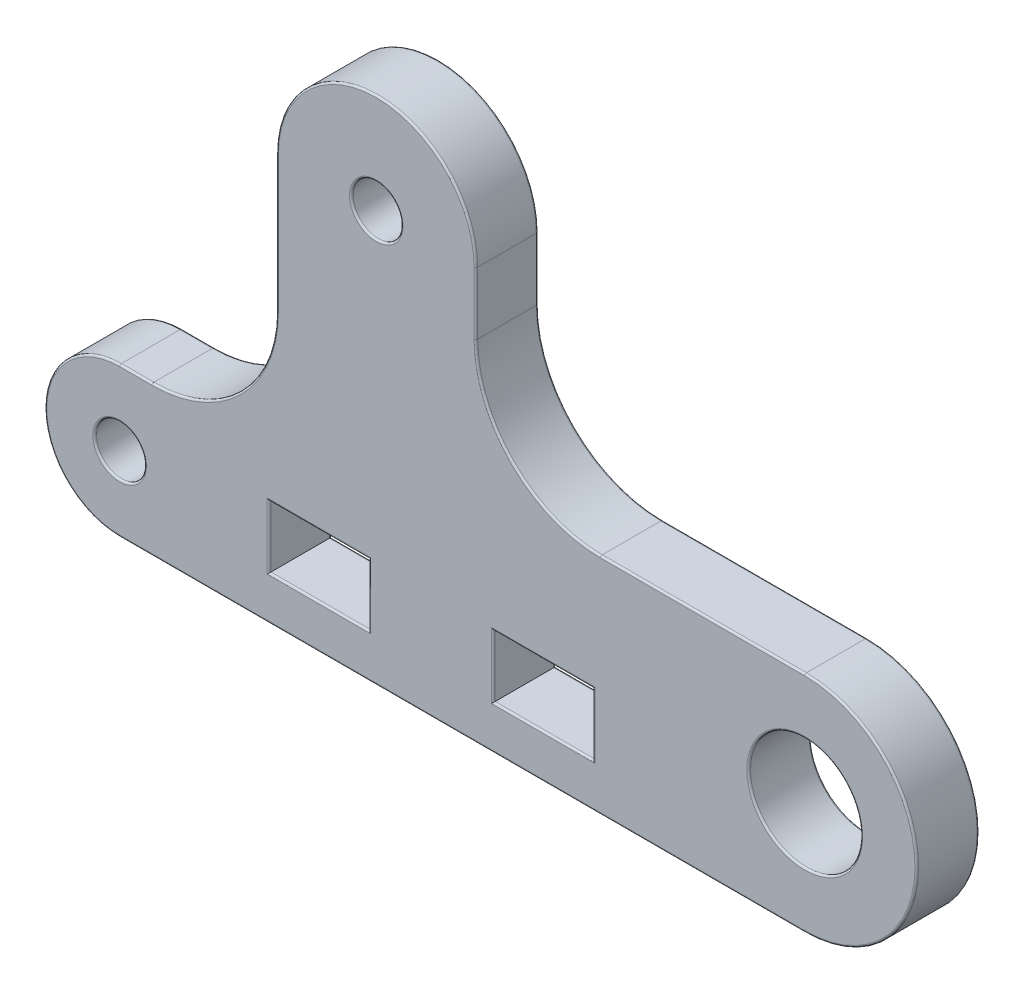
SolidWorks part; units mm, degrees
ref_plane "Front Plane" through (0, 0, 0) normal (0, 0, 1) x (1, 0, 0)
ref_plane "Top Plane" through (0, 0, 0) normal (0, 1, 0) x (1, 0, 0)
ref_plane "Right Plane" through (0, 0, 0) normal (1, 0, 0) x (0, 0, -1)
sketch "Sketch1" plane through (0, 0, 0) normal (0, 0, 1) x (1, 0, 0)
  line L0 (-27.5, 0) -> (27.5, 0)
  line L1 (-27.5, 12) -> (-24.9, 12)
  line L2 (-14.9, 22) -> (-14.9, 33)
  line L3 (1.1, 33) -> (1.1, 28)
  line L4 (11.1, 18) -> (27.5, 18)
  line L5 (-27.5, 6) -> (-15.5, 6) construction
  line L7 (-15.5, 8.5) -> (-7.5, 8.5)
  line L8 (-15.5, 8.5) -> (-15.5, 3.5)
  line L9 (-15.5, 3.5) -> (-7.5, 3.5)
  line L10 (-7.5, 8.5) -> (-7.5, 3.5)
  line L11 (2.5, 8.5) -> (10.5, 8.5)
  line L12 (2.5, 8.5) -> (2.5, 3.5)
  line L13 (2.5, 3.5) -> (10.5, 3.5)
  line L14 (10.5, 8.5) -> (10.5, 3.5)
  arc A0 (27.5, 0) -> (27.5, 18) centre (27.5, 9) ccw
  arc A1 (-27.5, 0) -> (-27.5, 12) centre (-27.5, 6) cw
  circle A2 centre (-27.5, 6) radius 2
  circle A3 centre (27.5, 9) radius 4.5
  circle A4 centre (-6.9, 33) radius 2
  circle A5 centre (-6.9, 33) radius 8 construction
  arc A6 (-14.9, 33) -> (1.1, 33) centre (-6.9, 33) cw
  arc A7 (1.1, 28) -> (11.1, 18) centre (11.1, 28) ccw
  arc A8 (-24.9, 12) -> (-14.9, 22) centre (-24.9, 22) ccw
  point P3 (0, 0)
  point P27 (-15.5, 6)
  dimension "D2" = 6
  dimension "D3" = 9
  dimension "D4" = 9
  dimension "D5" = 4
  dimension "D8" = 16
  dimension "D9" = 10
  dimension "D1" = 55
  dimension "D6" = 33
  dimension "D7" = 6.9
  dimension "D10" = 12
  dimension "D11" = 8
  dimension "D12" = 5
  dimension "D13" = 10
extrude "Boss-Extrude1" add sketch "Sketch1" along normal blind 5
fillet "Fillet1" radius 0.15 42 edges at (10.5, 6, 0) (6.5, 3.5, 0) (2.5, 6, 0) (6.5, 8.5, 0) (-7.5, 6, 0) (-11.5, 3.5, 0) (-15.5, 6, 0) (-11.5, 8.5, 0) (-25.5, 6, 0) (32, 9, 0) (0, 0, 0) (36.5, 9, 0) (19.3, 18, 0) (4.0289, 20.9289, 0) (1.1, 30.5, 0) (-6.9, 41, 0) (-14.9, 27.5, 0) (-17.8289, 14.9289, 0) (-26.2, 12, 0) (-33.5, 6, 0) (-4.9, 33, 0) (6.5, 3.5, 5) (10.5, 6, 5) (6.5, 8.5, 5) (2.5, 6, 5) (-25.5, 6, 5) (-4.9, 33, 5) (32, 9, 5) (-26.2, 12, 5) (-17.8289, 14.9289, 5) (-14.9, 27.5, 5) (-6.9, 41, 5) (1.1, 30.5, 5) (4.0289, 20.9289, 5) (19.3, 18, 5) (36.5, 9, 5) (0, 0, 5) (-33.5, 6, 5) (-11.5, 3.5, 5) (-7.5, 6, 5) (-11.5, 8.5, 5) (-15.5, 6, 5)
